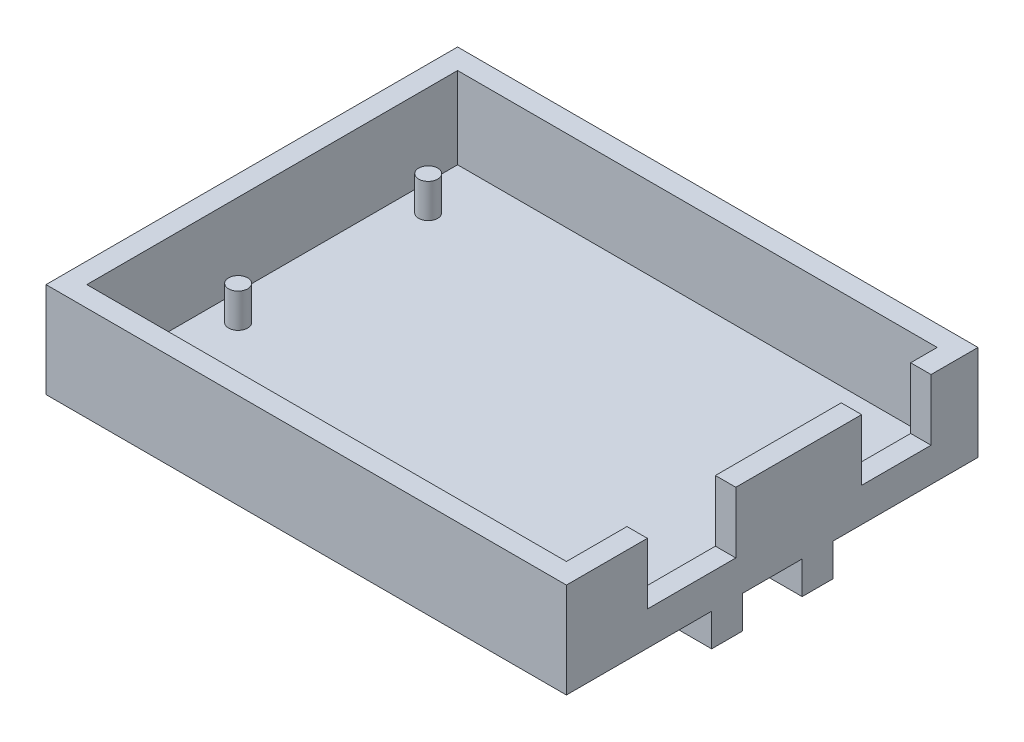
SolidWorks part; units mm, degrees
ref_plane "Front Plane" through (0, 0, 0) normal (0, 0, 1) x (1, 0, 0)
ref_plane "Top Plane" through (0, 0, 0) normal (0, 1, 0) x (1, 0, 0)
ref_plane "Right Plane" through (0, 0, 0) normal (1, 0, 0) x (0, 0, -1)
sketch "Sketch1" plane through (0, 0, 0) normal (0, 1, 0) x (1, 0, 0)
  line L1 (-38.25, -30.25) -> (38.25, -30.25)
  line L2 (-38.25, -30.25) -> (-38.25, 30.25)
  line L3 (-38.25, 30.25) -> (38.25, 30.25)
  line L4 (38.25, -30.25) -> (38.25, 30.25)
  line L5 (-38.25, -30.25) -> (38.25, 30.25) construction
  line L6 (-38.25, 30.25) -> (38.25, -30.25) construction
  point P0 (0, 0)
  dimension "D1" = 76.5
  dimension "D2" = 60.5
extrude "Boss-Extrude1" add sketch "Sketch1" along normal blind 14
sketch "Sketch2" plane through (0, 14, 0) normal (0, 1, 0) x (1, 0, 0)
  line L5 (-35.25, 27.25) -> (35.25, 27.25)
  line L6 (-35.25, 27.25) -> (-35.25, -27.25)
  line L7 (-35.25, -27.25) -> (35.25, -27.25)
  line L8 (35.25, 27.25) -> (35.25, -27.25)
  line L9 (-35.25, 27.25) -> (35.25, -27.25) construction
  line L10 (-35.25, -27.25) -> (35.25, 27.25) construction
  point P0 (0, 0)
  dimension "D1" = 70.5
  dimension "60" = 54.5
extrude "Cut-Extrude1" cut sketch "Sketch2" against normal blind 12
sketch "Sketch4" plane through (38.25, 0, 0) normal (1, 0, 0) x (0, 0, -1)
  line L0 (30.25, 5) -> (27.25, 5) construction
  line L1 (-30.25, 14) -> (-30.25, 0) construction
  line L2 (-18.35, 14) -> (-18.35, 5)
  line L7 (-30.25, 14) -> (30.25, 14) construction
  line L8 (-18.35, 5) -> (-5.35, 5)
  line L9 (-18.35, 14) -> (-5.35, 14)
  line L10 (-5.35, 14) -> (-5.35, 5)
  line L13 (-5.35, 5) -> (13.15, 5) construction
  line L14 (23.35, 14) -> (13.15, 14)
  line L15 (23.35, 14) -> (23.35, 5)
  line L16 (23.35, 5) -> (13.15, 5)
  line L17 (13.15, 14) -> (13.15, 5)
  line L21 (-30.25, 5) -> (-27.25, 5) construction
  line L22 (-27.25, 5) -> (-18.35, 5) construction
  line L23 (30.25, 14) -> (30.25, 0) construction
  line L24 (27.25, 5) -> (23.35, 5) construction
  dimension "D1" = 13
  dimension "D2" = 9
  dimension "D3" = 10.2
  dimension "D4" = 3
  dimension "D5" = 3
  dimension "D6" = 18.5
  dimension "D7" = 8.9
  dimension "D8" = 3.9
extrude "Cut-Extrude2" cut sketch "Sketch4" against normal up to next
sketch "Sketch5" plane through (0, 0, 0) normal (0, -1, 0) x (1, 0, 0)
  line L0 (0, -4.45) -> (0, 4.45) construction
  line L1 (-38.25, -30.25) -> (-38.25, 30.25) construction
  line L2 (-38.25, 4.4) -> (38.25, 4.4)
  line L3 (-38.25, 4.4) -> (-38.25, 8.9)
  line L4 (-38.25, 8.9) -> (38.25, 8.9)
  line L5 (38.25, 4.4) -> (38.25, 8.9)
  line L6 (38.25, 30.25) -> (38.25, -30.25) construction
  point P4 (0, 0)
  dimension "D1" = 4.5
  dimension "D2" = 8.9
extrude "Boss-Extrude3" add sketch "Sketch5" along normal blind 4.8
mirror "Mirror1" about plane through (0, 0, 0) normal (0, 0, 1) of "Boss-Extrude3"
sketch "Sketch6" plane through (0, 2, 0) normal (0, 1, 0) x (1, 0, 0)
  line L0 (35.25, 0) -> (-31.29, 0) construction
  line L1 (35.25, -27.25) -> (35.25, 27.25) construction
  line L2 (-31.29, -27.25) -> (-31.29, -8.97) construction
  line L3 (-35.25, -27.25) -> (35.25, -27.25) construction
  line L4 (-31.29, -8.97) -> (-31.29, 18.97) construction
  circle A0 centre (-31.29, -8.97) radius 1.4
  circle A1 centre (-31.29, 18.97) radius 1.4
  dimension "D4" = 2.8
  dimension "D5" = 2.8
  dimension "D1" = 66.54
  dimension "D2" = 18.28
  dimension "D3" = 27.94
extrude "Boss-Extrude4" add sketch "Sketch6" along normal blind 5
